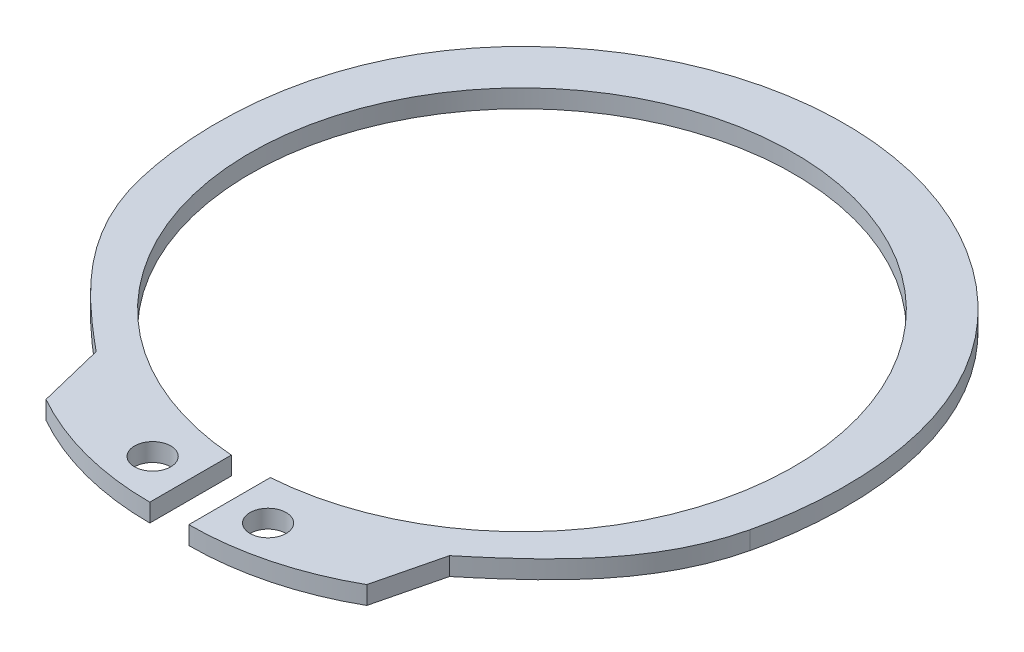
SolidWorks part; units mm, degrees
ref_plane "Ön Düzlem" through (0, 0, 0) normal (0, 0, 1) x (1, 0, 0)
ref_plane "Üst Düzlem" through (0, 0, 0) normal (0, 1, 0) x (1, 0, 0)
ref_plane "Sağ Düzlem" through (0, 0, 0) normal (1, 0, 0) x (0, 0, -1)
sketch "Çizim1" plane through (0, 0, 0) normal (0, 1, 0) x (1, 0, 0)
  line L0 (-2.1519, -29.9227) -> (-2.1519, -38.9227)
  line L1 (-17.702, -34.8276) -> (-19.4994, -27.495)
  line L2 (0, 0) -> (0, 41.8633)
  line L3 (17.702, -34.8276) -> (19.4994, -27.495)
  line L4 (2.1519, -29.9227) -> (2.1519, -38.9227)
  line L5 (10.8302, -34.3903) -> (14.6395, -34.3903)
  line L6 (6.3689, -30.3125) -> (6.3689, -25.5508)
  circle A0 centre (0, 0) radius 30
  arc A2 (-2.1519, -38.9227) -> (-17.702, -34.8276) centre (-2.1519, -7.3516) cw
  circle A3 centre (-6.3689, -34.3903) radius 2
  circle A4 centre (6.3689, -34.3903) radius 2
  arc A5 (2.1519, -38.9227) -> (17.702, -34.8276) centre (2.1519, -7.3516) ccw
  arc A6 (24.5646, 25.767) -> (-24.5646, 25.767) centre (0, 0) ccw
  spline S0 degree 3 poles (-24.5646, 25.767) (-32.251, 18.4393) (-35.719, 6.2167) (-34.2765, -5.5417) (-33.6081, -8.4147) knots 0 0 0 0 0.765438 1 1 1 1
  spline S1 degree 3 poles (-33.6081, -8.4147) (-31.6082, -17.0109) (-25.4328, -22.5692) (-19.4994, -27.495) knots 0 0 0 0 1 1 1 1
  spline S2 degree 3 poles (24.5646, 25.767) (32.251, 18.4393) (35.719, 6.2167) (34.2765, -5.5417) (33.6081, -8.4147) knots 0 0 0 0 0.765438 1 1 1 1
  spline S3 degree 3 poles (33.6081, -8.4147) (31.6082, -17.0109) (25.4328, -22.5692) (19.4994, -27.495) knots 0 0 0 0 1 1 1 1
  dimension "D1" = 60
  dimension "D2" = 4
  dimension "D3" = 9
extrude "Yükseklik-Ekstrüzyon1" add sketch "Çizim1" along normal blind 2 contours S0 S1 L1 A2 L0 A0 L2 A6 A3 | S3 S2 A6 L2 A0 L4 A5 L3 A4
